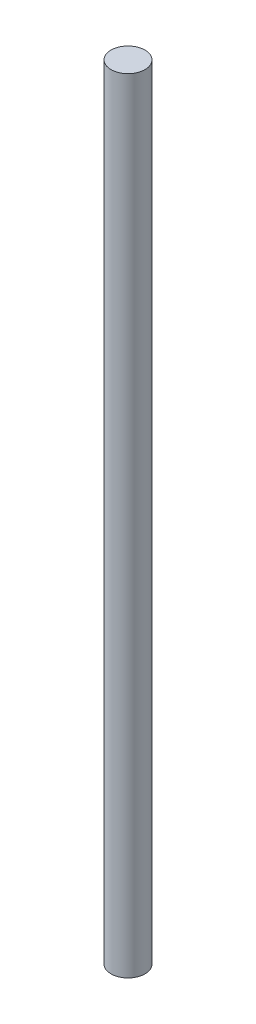
SolidWorks part; units mm, degrees
ref_plane "Front Plane" through (0, 0, 0) normal (0, 0, 1) x (1, 0, 0)
ref_plane "Top Plane" through (0, 0, 0) normal (0, 1, 0) x (1, 0, 0)
ref_plane "Right Plane" through (0, 0, 0) normal (1, 0, 0) x (0, 0, -1)
sketch "Sketch1" plane through (0, 0, 0) normal (0, 1, 0) x (1, 0, 0)
  circle A0 centre (0, 0) radius 1.651
extrude "Boss-Extrude1" add sketch "Sketch1" along normal blind 76.2
